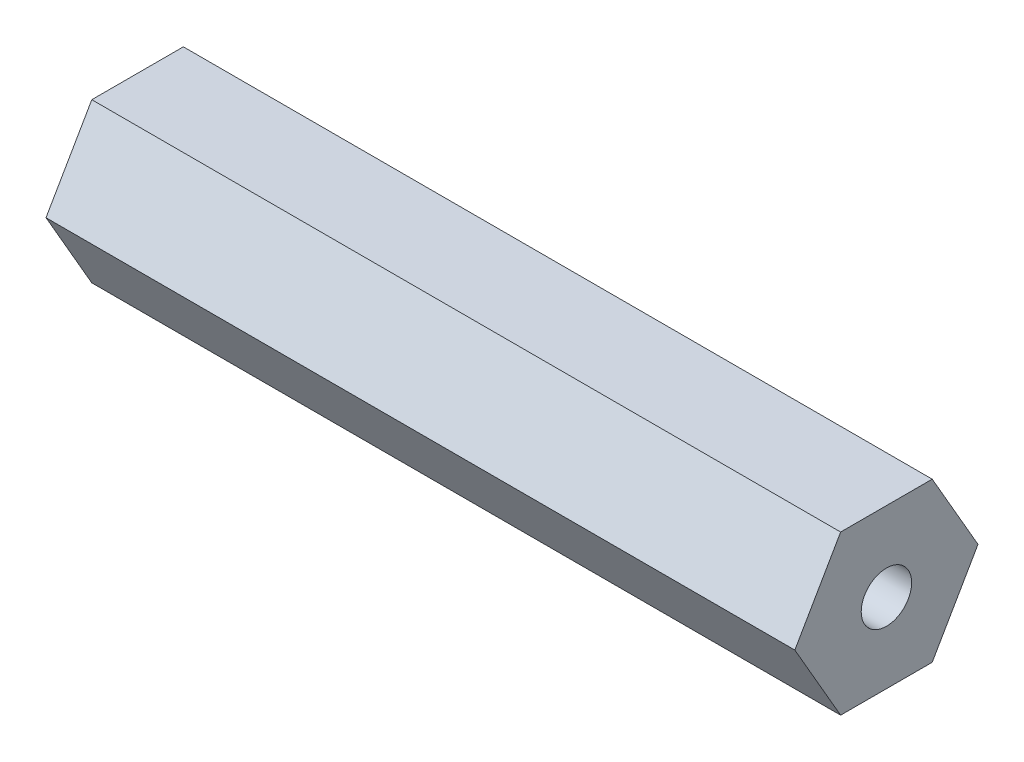
SolidWorks part; units mm, degrees
ref_plane "Front Plane" through (0, 0, 0) normal (0, 0, 1) x (1, 0, 0)
ref_plane "Top Plane" through (0, 0, 0) normal (0, 1, 0) x (1, 0, 0)
ref_plane "Right Plane" through (0, 0, 0) normal (1, 0, 0) x (0, 0, -1)
sketch "Sketch1" plane through (0, 0, 0) normal (1, 0, 0) x (0, 0, -1)
  line L1 (7.3323, 0) -> (3.6662, 6.35)
  line L2 (3.6662, 6.35) -> (-3.6662, 6.35)
  line L3 (-3.6662, 6.35) -> (-7.3323, 0)
  line L4 (-7.3323, 0) -> (-3.6662, -6.35)
  line L5 (-3.6662, -6.35) -> (3.6662, -6.35)
  line L6 (3.6662, -6.35) -> (7.3323, 0)
  circle A0 centre (0, 0) radius 6.35 construction
  circle A1 centre (0, 0) radius 2.0193
  point P10 (7.3323, 0)
  dimension "D1" = 12.7
  dimension "D2" = 4.0386
extrude "Boss-Extrude1" add sketch "Sketch1" along normal blind 59.9567
